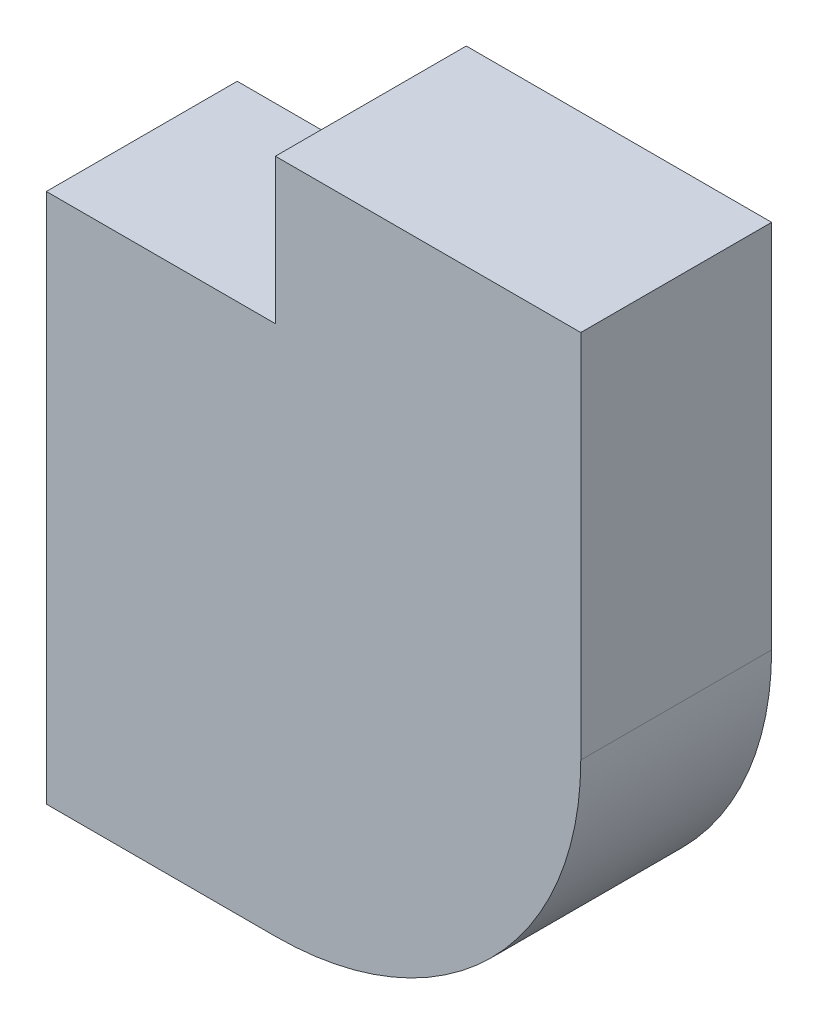
SolidWorks part; units mm, degrees
material "PBT General Purpose"
ref_plane "Front Plane" through (0, 0, 0) normal (0, 0, 1) x (1, 0, 0)
ref_plane "Top Plane" through (0, 0, 0) normal (0, 1, 0) x (1, 0, 0)
ref_plane "Right Plane" through (0, 0, 0) normal (1, 0, 0) x (0, 0, -1)
sketch "frame_outline" plane through (0, 0, 0) normal (0, 0, 1) x (1, 0, 0)
  line L110 (0, 0) -> (0, 0.695)
  line L121 (0.7, 0) -> (0, 0)
  line L122 (0, 0.695) -> (0.3, 0.695)
  line L123 (0.3, 0.695) -> (0.3, 0.885)
  line L124 (0.3, 0.885) -> (0.7, 0.885)
  line L125 (0.7, 0.885) -> (0.7, 0.695)
  line L126 (0.7, 0.695) -> (0.7, 0)
  dimension "D1" = 0.695
  dimension "D2" = 0.3
  dimension "D3" = 0.4
  dimension "D4" = 0.19
extrude "Boss-Extrude1" add sketch "frame_outline" along normal mid plane 0.25
fillet "Fillet1" radius 0.4 1 edges at (0.7, 0, 0)
equation "\"t\"= 0.25'thickness of the sheets"
equation "\"t_cf\" = 0.115'thickness of single carbon fiber layer"
equation "\"t_kapton\" = 0.025'thickness of single Kapton flex layer"
equation "\"t_fr4\" = 0.1'thickness of FR4 with copper layer"
equation "\"joint_flex\"= 0.1'Width of flextures gap"
equation "\"joint_flex_eff\"= 0.02'Width of flecture after castelation"
equation "\"joint_fold\"= 0.2'Width of folding joints for 90deg fold"
equation "\"gap_tolerance\"= 0.002'Width to have interfecence fit between carbon fiber inserts"
equation "\"assemble_angle\"= 90'Angle of assembly parts"
equation "\"D1@Boss-Extrude1\"=\"t\""
equation "\"link_lift\"= 0.5'Actuation linkage amplification for the lift motion"
equation "\"link_swing\"= 0.45'Actuation linkage amplification for the swing motion"
equation "\"D1@frame_outline\"=0.695"
equation "\"D4@frame_outline\"=\"t\"-0.06"
